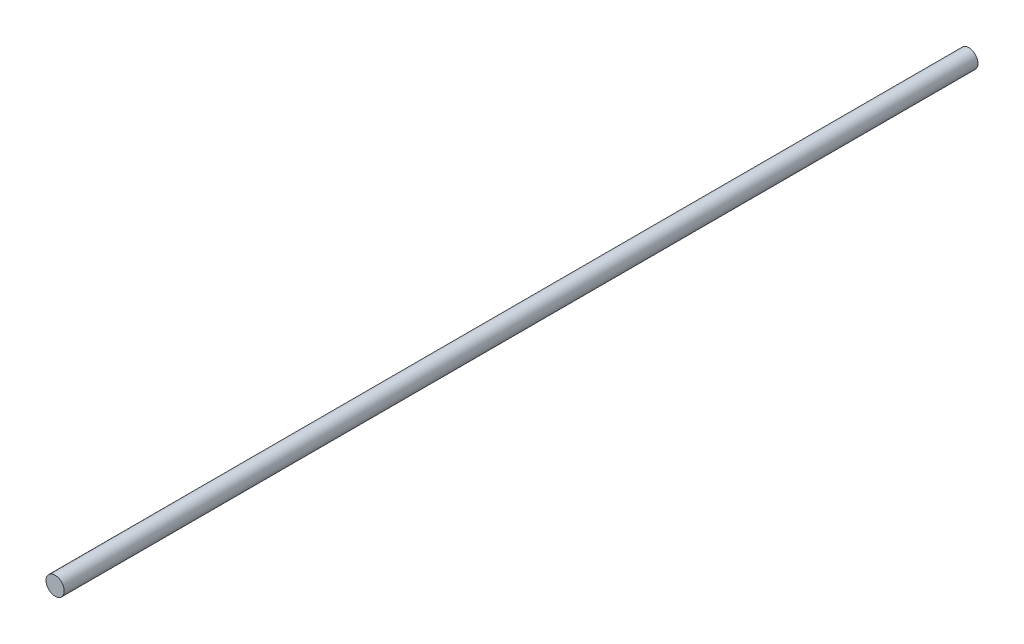
SolidWorks part; units mm, degrees
ref_plane "Ebene vorne" through (0, 0, 0) normal (0, 0, 1) x (1, 0, 0)
ref_plane "Ebene oben" through (0, 0, 0) normal (0, 1, 0) x (1, 0, 0)
ref_plane "Ebene rechts" through (0, 0, 0) normal (1, 0, 0) x (0, 0, -1)
sketch "Skizze1" plane through (0, 0, 0) normal (0, 0, 1) x (1, 0, 0)
  circle A0 centre (0, 0) radius 1.5
  dimension "D1" = 3
extrude "Aufsatz-Linear austragen1" add sketch "Skizze1" along normal blind 150
cosmetic thread "Gewindedarstellung1" parameters "D1"=12, "D2"=2.439
cosmetic thread "Gewindedarstellung2" parameters "D1"=12, "D2"=2.439
